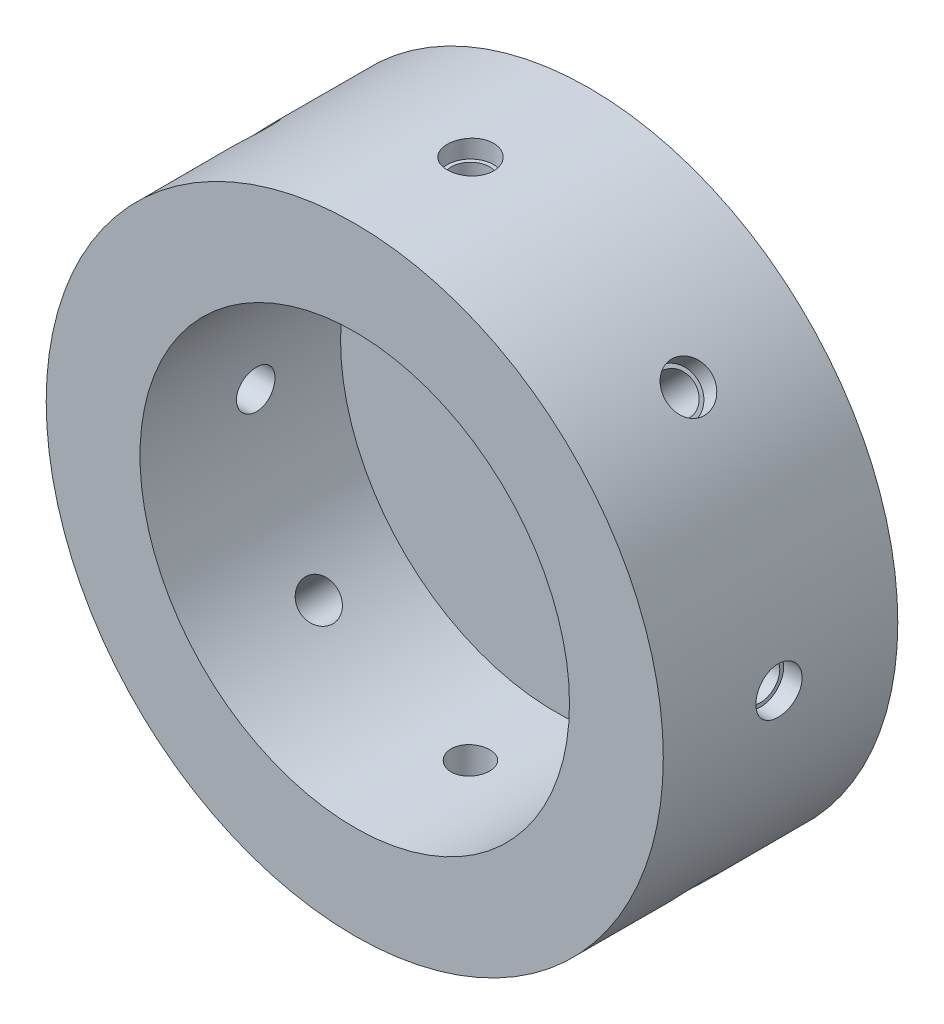
SolidWorks part; units mm, degrees
other "Markup1"
sketch "Sketch8" plane through (110, 110, 0) normal (0.0901, 0.1911, 0.9774) x (0.9758, -0.2132, -0.0483)
ref_plane "Front Plane" through (0, 0, 0) normal (0, 0, 1) x (1, 0, 0)
ref_plane "Top Plane" through (0, 0, 0) normal (0, 1, 0) x (1, 0, 0)
ref_plane "Right Plane" through (0, 0, 0) normal (1, 0, 0) x (0, 0, -1)
sketch "Sketch2" plane through (0, 0, 0) normal (0, 0, 1) x (1, 0, 0)
  circle A0 centre (0, 0) radius 100
  circle A1 centre (0, 0) radius 69.6
  dimension "D1" = 200
  dimension "D2" = 139.2
extrude "Boss-Extrude1" add sketch "Sketch2" against normal blind 75
sketch "Sketch3" plane through (0, 0, -75) normal (0, 0, -1) x (-1, 0, 0)
  circle A0 centre (0, 0) radius 100
  circle A1 centre (0, 0) radius 10
  dimension "D1" = 20
  dimension "D2" = 200
extrude "Boss-Extrude2" add sketch "Sketch3" along normal blind 1 and the other way blind 10
ref_plane "Plane1" through (0, -100, 0) normal (0, 1, 0) x (1, 0, 0)
sketch "Sketch4" plane through (0, -100, 0) normal (0, 1, 0) x (1, 0, 0)
  circle A0 centre (0, 37.5) radius 7.5
extrude "Cut-Extrude4" cut sketch "Sketch4" along normal blind 6
sketch "Sketch7" plane through (0, -94, 0) normal (0, -1, 0) x (1, 0, 0)
  circle A0 centre (0, -37.5) radius 6.25
extrude "Cut-Extrude5" cut sketch "Sketch7" against normal blind 50
pattern_circular "CirPattern1" count 8 over 360 about axis through (0, 0, 0) along (0, 0, 1) of "Cut-Extrude5", "Cut-Extrude4"
